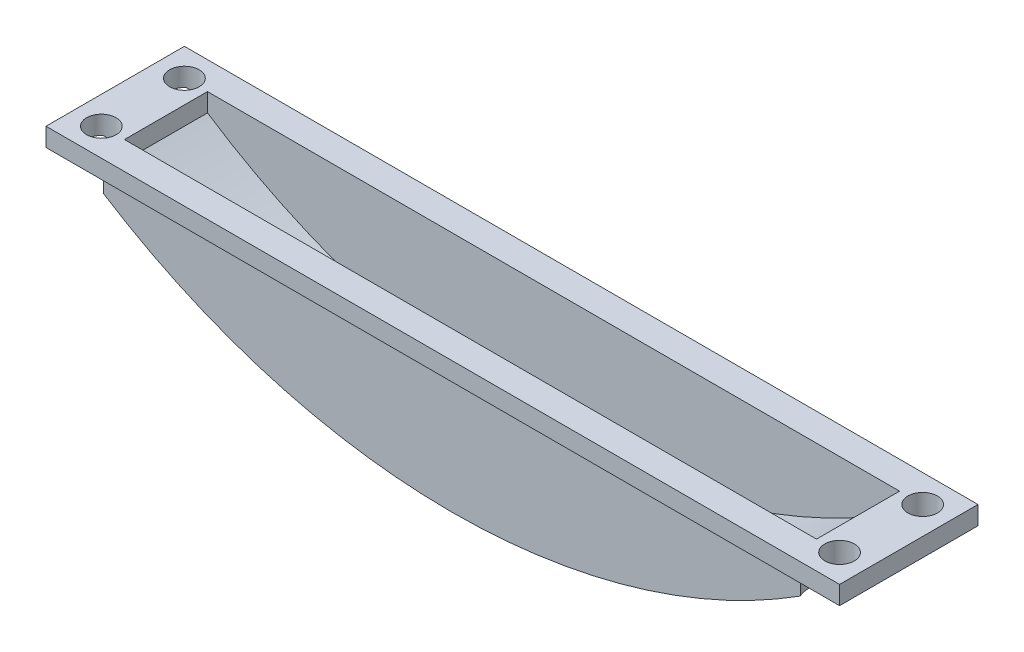
SolidWorks part; units mm, degrees
material "ABS"
ref_plane "前视基准面" through (0, 0, 0) normal (0, 0, 1) x (1, 0, 0)
ref_plane "上视基准面" through (0, 0, 0) normal (0, 1, 0) x (1, 0, 0)
ref_plane "右视基准面" through (0, 0, 0) normal (1, 0, 0) x (0, 0, -1)
other "Configuration Table"
sketch "草图3" plane through (0, 0, 0) normal (0, 1, 0) x (1, 0, 0)
  line L0 (-3, 12) -> (83, 12)
  line L1 (0, 0) -> (80, 0) construction
  line L2 (0, 0) -> (0, 9) construction
  line L3 (0, 9) -> (80, 9) construction
  line L4 (80, 0) -> (80, 9) construction
  line L5 (83, -3) -> (83, 12)
  line L6 (-3, -3) -> (83, -3)
  line L7 (-3, -3) -> (-3, 12)
  circle A0 centre (0, 9) radius 1.6 construction
  circle A1 centre (80, 9) radius 1.6 construction
  circle A2 centre (80, 0) radius 1.6 construction
  circle A3 centre (0, 0) radius 1.6 construction
  dimension "D3" = 3.2
  dimension "D1" = 9
  dimension "D2" = 80
  dimension "D4" = 3
extrude "凸台-拉伸1" add sketch "草图3" along normal blind 2
sketch "草图5" plane through (0, 0, 3) normal (0, 0, 1) x (1, 0, 0)
  line L0 (-3, 2) -> (83, 2) construction
  line L3 (2.5, 0) -> (-1.0264, 0)
  line L5 (77.5, 0) -> (81.0264, 0)
  line L7 (-3, 0) -> (83, 0) construction
  line L8 (-3.6711, 2) -> (83.6711, 2) construction
  line L9 (2.5, 0) -> (77.5, 0) construction
  arc A0 (2.5, 0) -> (77.5, 0) centre (40, 57) ccw
  arc A1 (-1.0264, 0) -> (81.0264, 0) centre (40, 57) ccw
  arc A2 (2.5, 0) -> (77.5, 0) centre (40, 57) ccw construction
  arc A3 (-3.6711, 2) -> (83.6711, 2) centre (40, 57) ccw construction
  point P0 (40, 2)
  point P1 (85.1403, 2)
  point P8 (82.6348, 1)
  point P13 (-3, 0)
  point P16 (40, 38.3193)
  point P18 (-6.0814, 2.5513)
  point P19 (-3, 0)
  point P20 (-3, 0)
  point P22 (83, 0)
  point P23 (83, 0)
  point P24 (0, 0)
  point P25 (40, 60.3174)
  point P26 (81.3989, 0)
  dimension "D3" = 2
  dimension "D1" = 75
  dimension "D2" = 55
extrude "凸台-拉伸2" add sketch "草图5" against normal blind 9 from offset 3 offset against normal yes
sketch "草图6" plane through (0, 0, 0) normal (0, 0, 1) x (1, 0, 0)
  line L0 (-1.0264, 0) -> (81.0264, 0)
  line L1 (-3, 0) -> (83, 0) construction
  line L2 (2.5, 0) -> (-1.0264, 0) construction
  arc A0 (-1.0264, 0) -> (81.0264, 0) centre (40, 57) ccw
  arc A3 (-1.0264, 0) -> (81.0264, 0) centre (40, 57) ccw construction
  point P8 (81.0264, 0)
  point P11 (-1.0264, 0)
  point P14 (-1.0264, 0)
extrude "凸台-拉伸3" add sketch "草图6" along normal blind 2
ref_plane "基准面1" through (0, 0, -4.5) normal (0, 0, 1) x (1, 0, 0)
mirror "镜向1" about plane through (0, 0, -4.5) normal (0, 0, 1) of "凸台-拉伸3"
sketch "草图7" plane through (0, 2, 0) normal (0, 1, 0) x (1, 0, 0)
  line L8 (2.5, 9) -> (2.5, 0)
  line L9 (0, 9) -> (80, 9) construction
  line L10 (0, 0) -> (80, 0) construction
  line L11 (2.5, 0) -> (77.5, 0)
  line L12 (77.5, 0) -> (77.5, 9)
  line L13 (77.5, 9) -> (2.5, 9)
  point P3 (2.128, 0)
  point P9 (0, 0)
extrude "切除-拉伸1" cut sketch "草图7" against normal up to next
sketch "草图8" plane through (0, 2, 0) normal (0, 1, 0) x (1, 0, 0)
  circle A0 centre (80, 0) radius 1.6 construction
  circle A1 centre (80, 9) radius 1.6 construction
  circle A2 centre (0, 0) radius 1.6 construction
  circle A3 centre (0, 9) radius 1.6 construction
  circle A4 centre (80, 0) radius 1.6
  circle A5 centre (80, 9) radius 1.6
  circle A6 centre (0, 0) radius 1.6
  circle A7 centre (0, 9) radius 1.6
extrude "切除-拉伸2" cut sketch "草图8" against normal through all
sketch "草图9" plane through (0, 2, 0) normal (0, 1, 0) x (1, 0, 0)
  circle A0 centre (0, 9) radius 3
  circle A1 centre (0, 0) radius 3
  circle A2 centre (80, 0) radius 3
  circle A3 centre (80, 9) radius 3
  dimension "D1" = 6
extrude "切除-拉伸3" cut sketch "草图9" against normal through all from offset 3
